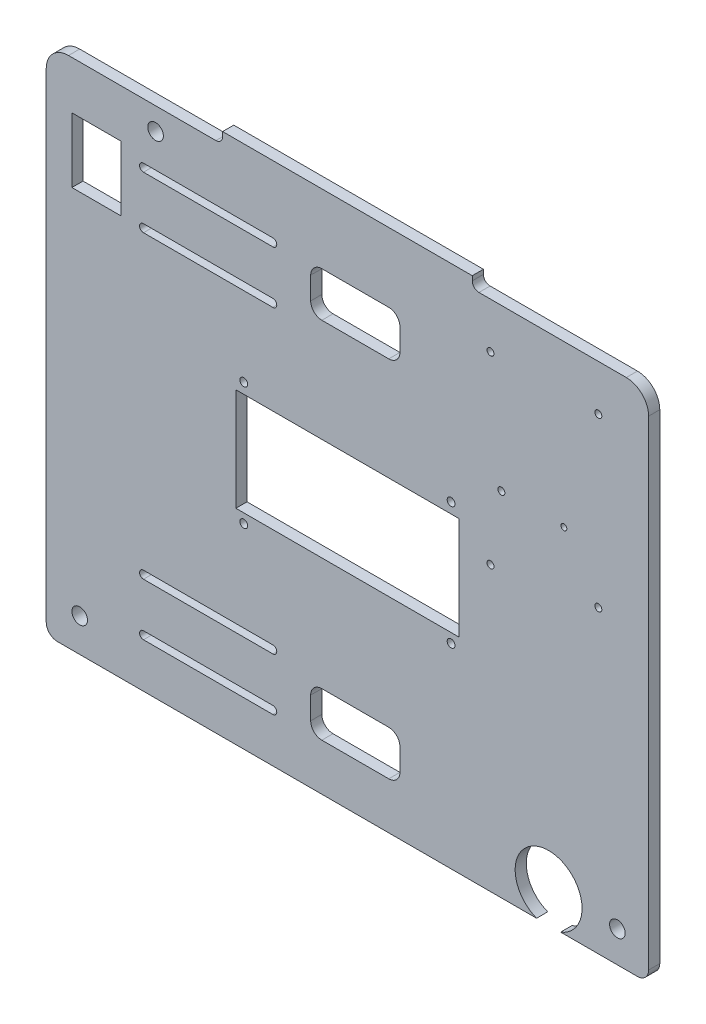
SolidWorks part; units mm, degrees
material "Alumina"
ref_plane "Front Plane" through (0, 0, 0) normal (0, 0, 1) x (1, 0, 0)
ref_plane "Top Plane" through (0, 0, 0) normal (0, 1, 0) x (1, 0, 0)
ref_plane "Right Plane" through (0, 0, 0) normal (1, 0, 0) x (0, 0, -1)
sketch "Sketch1" plane through (0, 0, 0) normal (0, 0, 1) x (1, 0, 0)
  line L1 (-135, 130) -> (135, 130)
  line L2 (-135, 130) -> (-135, -130)
  line L3 (-135, -130) -> (135, -130)
  line L4 (135, 130) -> (135, -130)
  line L5 (-135, 130) -> (135, -130) construction
  line L6 (-135, -130) -> (135, 130) construction
  point P0 (0, 0)
  dimension "D1" = 270
  dimension "D2" = 260
extrude "Boss-Extrude1" add sketch "Sketch1" along normal blind 5
sketch "Sketch2" plane through (0, 0, 0) normal (0, 0, -1) x (-1, 0, 0)
  circle A0 centre (120, -115) radius 3.5
  circle A1 centre (86, 90) radius 3.5
  circle A3 centre (-121, -116) radius 3.5
  dimension "D1" = 7
  dimension "D2" = 7
extrude "Cut-Extrude1" cut sketch "Sketch2" against normal through all
sketch "Sketch3" plane through (0, 0, 5) normal (0, 0, 1) x (1, 0, 0)
  circle A0 centre (90.1724, -116) radius 15
  dimension "D1" = 30
extrude "Cut-Extrude2" cut sketch "Sketch3" against normal through all
fillet "Fillet1" radius 5 4 edges at (135, -130, 2.5) (135, 130, 2.5) (-135, 130, 2.5) (-135, -130, 2.5)
sketch "Sketch4" plane through (0, 0, 0) normal (0, 0, -1) x (-1, 0, 0)
  line L0 (135, 100) -> (-135, 100)
  line L1 (135, 125) -> (135, -125) construction
  line L2 (-135, -125) -> (-135, 125) construction
  line L3 (95.6, 100) -> (90.2, 100)
  line L4 (-130, 130) -> (130, 130) construction
  line L5 (-135, 100) -> (-135, 125)
  line L6 (-130, 130) -> (130, 130)
  line L7 (135, 125) -> (135, 100)
  arc A0 (-130, 130) -> (-135, 125) centre (-130, 125) ccw construction
  arc A1 (135, 125) -> (130, 130) centre (130, 125) ccw construction
  arc A2 (-130, 130) -> (-135, 125) centre (-130, 125) ccw
  arc A3 (135, 125) -> (130, 130) centre (130, 125) ccw
  line M6 (-135, 125) -> (-135, -125)
  line M12 (135, -125) -> (135, 125)
  arc M13 (135, 125) -> (130, 130) centre (130, 125) ccw
  line M14 (130, 130) -> (-130, 130)
  arc M15 (-130, 130) -> (-135, 125) centre (-130, 125) ccw
extrude "Cut-Extrude3" cut sketch "Sketch4" against normal through all contours L0 M12 M13 M14 M15 M6
sketch "Sketch6" plane through (0, 0, 5) normal (0, 0, 1) x (1, 0, 0)
  line L0 (-135, 100) -> (135, 100) construction
  line L1 (-55.95, 100) -> (55.95, 100)
  line L2 (-55.95, 100) -> (-55.95, 105)
  line L3 (-55.95, 105) -> (55.95, 105)
  line L4 (55.95, 100) -> (55.95, 105)
  point P4 (0, 100)
  point P7 (0, 100)
  dimension "D1" = 111.9
  dimension "D2" = 5
extrude "Boss-Extrude2" add sketch "Sketch6" against normal up to surface (5 mm away) up to face at (117.5, -116, 0)
fillet "Fillet2" radius 10 2 edges at (135, 100, 2.5) (-135, 100, 2.5)
sketch "Sketch9" plane through (0, 0, 5) normal (0, 0, 1) x (1, 0, 0)
  line L1 (-123.5, 78.5) -> (-101.5, 78.5)
  line L2 (-123.5, 78.5) -> (-123.5, 49.5)
  line L3 (-123.5, 49.5) -> (-101.5, 49.5)
  line L4 (-101.5, 78.5) -> (-101.5, 49.5)
  line L5 (-123.5, 78.5) -> (-101.5, 49.5) construction
  line L6 (-123.5, 49.5) -> (-101.5, 78.5) construction
  point P0 (-112.5, 64)
extrude "Cut-Extrude5" cut sketch "Sketch9" against normal through all
sketch "Sketch10" plane through (0, 0, 0) normal (0, 0, -1) x (-1, 0, 0)
  circle A0 centre (-46.46, 12.46) radius 1.75
  circle A1 centre (46.46, 12.46) radius 1.75
  circle A2 centre (-46.46, -42.46) radius 1.75
  circle A3 centre (46.46, -42.46) radius 1.75
extrude "Cut-Extrude6" cut sketch "Sketch10" against normal through all
sketch "Sketch11" plane through (0, 0, 5) normal (0, 0, 1) x (1, 0, 0)
  line L1 (-50, 7.7465) -> (50, 7.7465)
  line L2 (-50, 7.7465) -> (-50, -38.2535)
  line L3 (-50, -38.2535) -> (50, -38.2535)
  line L4 (50, 7.7465) -> (50, -38.2535)
  line L5 (-50, 7.7465) -> (50, -38.2535) construction
  line L6 (-50, -38.2535) -> (50, 7.7465) construction
  point P0 (0, -15.2535)
  dimension "D1" = 46
  dimension "D2" = 100
extrude "Cut-Extrude7" cut sketch "Sketch11" against normal through all
sketch "Sketch12" plane through (0, 0, 5) normal (0, 0, 1) x (1, 0, 0)
  circle A2 centre (112.46, 4.3944) radius 1.5621
  circle A3 centre (64.1238, -3.0986) radius 1.5621
  circle A4 centre (69.0023, 27.9021) radius 1.5621
  circle A5 centre (97.0185, 27.9021) radius 1.3153
  circle A6 centre (112.46, 79.5276) radius 1.5621
  circle A7 centre (64.1238, 79.5276) radius 1.5621
extrude "Cut-Extrude8" cut sketch "Sketch12" against normal through all
sketch "Sketch13" plane through (0, 0, 0) normal (0, 0, -1) x (-1, 0, 0)
  line L0 (101.5, 49.5) -> (101.5, 78.5) construction
  line L3 (125, 100) -> (55.95, 100) construction
  line L6 (33.419, 73.25) -> (91.4088, 73.25) construction
  line L7 (33.419, 75) -> (91.4088, 75)
  line L8 (33.419, 71.5) -> (91.4088, 71.5)
  line L9 (33.419, 49.75) -> (91.4088, 49.75) construction
  line L10 (33.419, 51.5) -> (91.4088, 51.5)
  line L11 (33.419, 48) -> (91.4088, 48)
  line L12 (-135, -17.5) -> (135, -17.5) construction
  line L15 (-135, -125) -> (-135, 90) construction
  line L16 (-23.5308, 74) -> (16.4692, 74)
  line L17 (-23.5308, 74) -> (-23.5308, 54)
  line L18 (-23.5308, 54) -> (16.4692, 54)
  line L19 (16.4692, 74) -> (16.4692, 54)
  line L20 (-23.5308, 74) -> (16.4692, 54) construction
  line L21 (-23.5308, 54) -> (16.4692, 74) construction
  line L26 (135, 90) -> (135, -125) construction
  line L27 (-23.5308, -89) -> (16.4692, -109) construction
  line L28 (-23.5308, -109) -> (16.4692, -89) construction
  line L29 (16.4692, -109) -> (16.4692, -89)
  line L30 (-23.5308, -89) -> (16.4692, -89)
  line L31 (-23.5308, -109) -> (-23.5308, -89)
  line L32 (-23.5308, -109) -> (16.4692, -109)
  line L33 (33.419, -84.75) -> (91.4088, -84.75) construction
  line L34 (33.419, -86.5) -> (91.4088, -86.5)
  line L35 (33.419, -83) -> (91.4088, -83)
  line L36 (33.419, -108.25) -> (91.4088, -108.25) construction
  line L37 (33.419, -110) -> (91.4088, -110)
  line L38 (33.419, -106.5) -> (91.4088, -106.5)
  arc A4 (33.419, 75) -> (33.419, 71.5) centre (33.419, 73.25) ccw
  arc A5 (91.4088, 71.5) -> (91.4088, 75) centre (91.4088, 73.25) ccw
  arc A6 (33.419, 51.5) -> (33.419, 48) centre (33.419, 49.75) ccw
  arc A7 (91.4088, 48) -> (91.4088, 51.5) centre (91.4088, 49.75) ccw
  arc A10 (33.419, -86.5) -> (33.419, -83) centre (33.419, -84.75) cw
  arc A11 (91.4088, -83) -> (91.4088, -86.5) centre (91.4088, -84.75) cw
  arc A12 (33.419, -110) -> (33.419, -106.5) centre (33.419, -108.25) cw
  arc A13 (91.4088, -106.5) -> (91.4088, -110) centre (91.4088, -108.25) cw
  point P0 (16.4692, 64)
  point P3 (101.5, 64)
  point P14 (62.4139, 73.25)
  point P21 (62.4139, 49.75)
  point P30 (-3.5308, -99)
  point P33 (62.4139, -84.75)
  point P35 (-3.5308, 64)
  point P45 (62.4139, -108.25)
  dimension "D1" = 1.75
  dimension "D2" = 20
  dimension "D3" = 25
  dimension "D4" = 40
  dimension "D5" = 20
extrude "Cut-Extrude9" cut sketch "Sketch13" against normal through all
fillet "Fillet3" radius 3 2 edges at (55.95, 100, 2.5) (-55.95, 100, 2.5)
fillet "Fillet6" radius 5 4 edges at (-16.4692, 54, 2.5) (-16.4692, 74, 2.5) (23.5308, 54, 2.5) (23.5308, 74, 2.5)
fillet "Fillet7" radius 5 4 edges at (-16.4692, -109, 2.5) (-16.4692, -89, 2.5) (23.5308, -89, 2.5) (23.5308, -109, 2.5)
